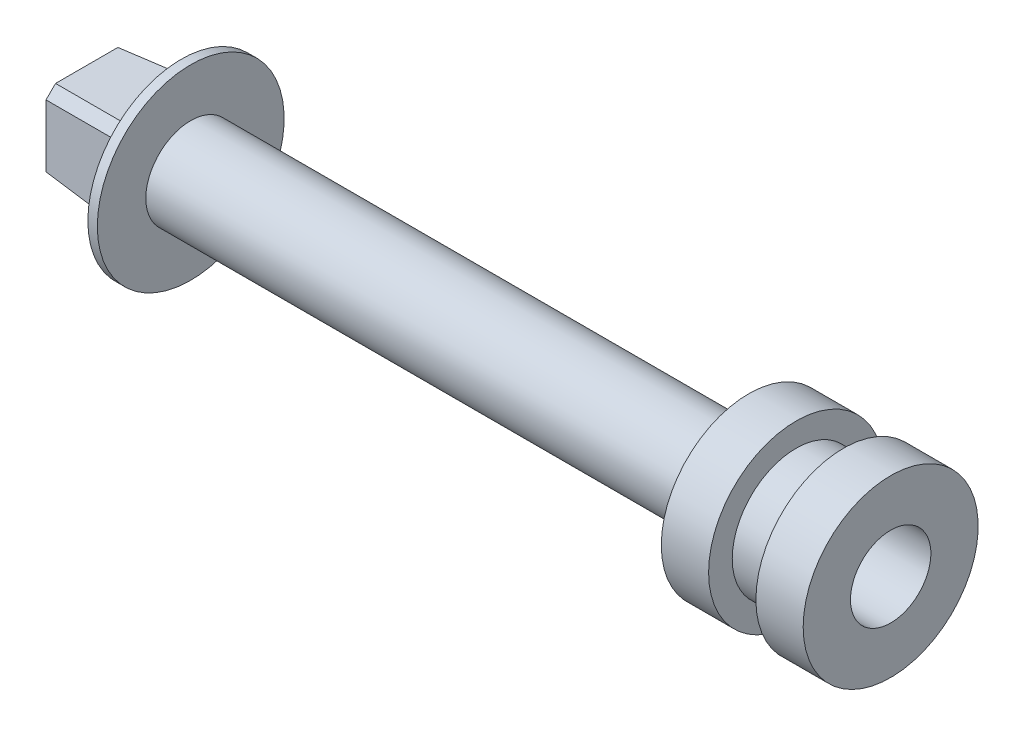
SolidWorks part; units mm, degrees
ref_plane "Plan de face" through (0, 0, 0) normal (0, 0, 1) x (1, 0, 0)
ref_plane "Plan de dessus" through (0, 0, 0) normal (0, 1, 0) x (1, 0, 0)
ref_plane "Plan de droite" through (0, 0, 0) normal (1, 0, 0) x (0, 0, -1)
sketch "Esquisse1" plane through (0, 0, 0) normal (0, 0, 1) x (1, 0, 0)
  line L0 (0, 0) -> (270, 0) construction
  line L1 (0, 0) -> (0, 39.5)
  line L2 (0, 39.5) -> (4, 39.5)
  line L3 (4, 39.5) -> (4, 19)
  line L4 (4, 19) -> (240, 19)
  line L5 (240, 19) -> (240, 37)
  line L6 (240, 37) -> (260, 37)
  line L7 (260, 37) -> (260, 27)
  line L8 (260, 27) -> (280, 27)
  line L9 (280, 27) -> (280, 37)
  line L10 (280, 37) -> (300, 37)
  line L11 (300, 37) -> (300, 17)
  line L12 (300, 17) -> (270, 17)
  line L13 (270, 17) -> (270, 0)
  line L14 (0, 0) -> (270, 0)
  point P1 (300, 27)
  point P17 (270, 8.5)
  point P18 (290, 37)
  dimension "D1" = 4
  dimension "D2" = 300
  dimension "D3" = 20
  dimension "D4" = 30
  dimension "D5" = 20
  dimension "D6" = 74
  dimension "D7" = 38
  dimension "D8" = 79
  dimension "D9" = 10
  dimension "D10" = 34
revolve "Révolution1" add sketch "Esquisse1" angle 360 about L0
sketch "Esquisse2" plane through (0, 0, 0) normal (-1, 0, 0) x (0, 0, 1)
  line L0 (20, 0) -> (0, 0) construction
  line L1 (-20, 20) -> (20, 20)
  line L2 (-20, 20) -> (-20, -20)
  line L3 (-20, -20) -> (20, -20)
  line L4 (20, 20) -> (20, -20)
  line L5 (0, 0) -> (0, 20) construction
  dimension "D1" = 40
extrude "Boss.-Extru.1" add sketch "Esquisse2" along normal blind 40 draft 4
chamfer "Chanfrein1" distance 4 angle 45 4 edges at (-20, -18.6015, -18.6015) (-20, -18.6015, 18.6015) (-20, 18.6015, -18.6015) (-20, 18.6015, 18.6015)
